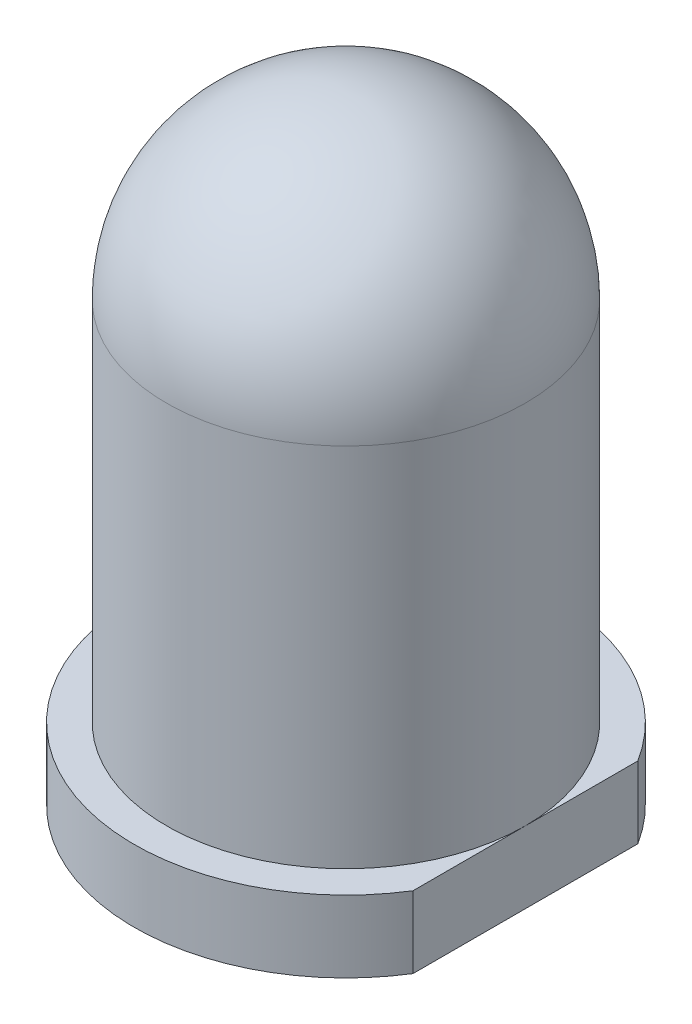
SolidWorks part; units mm, degrees
ref_plane "Plan de face" through (0, 0, 0) normal (0, 0, 1) x (1, 0, 0)
ref_plane "Plan de dessus" through (0, 0, 0) normal (0, 1, 0) x (1, 0, 0)
ref_plane "Plan de droite" through (0, 0, 0) normal (1, 0, 0) x (0, 0, -1)
sketch "Esquisse1" plane through (0, 0, 0) normal (0, 0, 1) x (1, 0, 0)
  line L0 (0, -2.358) -> (0, 10.3032) construction
  line L1 (0, 0) -> (2.95, 0)
  line L2 (2.95, 0) -> (2.95, 1)
  line L3 (2.95, 1) -> (2.5, 1)
  line L4 (2.5, 1) -> (2.5, 6.1)
  line L5 (0, 0) -> (0, 8.6)
  arc A0 (2.5, 6.1) -> (0, 8.6) centre (0, 6.1) ccw
  dimension "D4" = 2.5
  dimension "D1" = 5.9
  dimension "D2" = 1
  dimension "D3" = 8.6
revolve "Révolution1" add sketch "Esquisse1" angle 360 about L0
sketch "Esquisse2" plane through (0, 0, 0) normal (0, 1, 0) x (1, 0, 0)
  line L0 (2.5, -1.566) -> (2.5, 1.566)
  circle A0 centre (0, 0) radius 2.95 construction
  arc A1 (2.5, -1.566) -> (2.5, 1.566) centre (0, 0) ccw
  point P0 (2.95, 0)
  dimension "D1" = 0.45
extrude "Enlèv. mat.-Extru.1" cut sketch "Esquisse2" along normal through all
